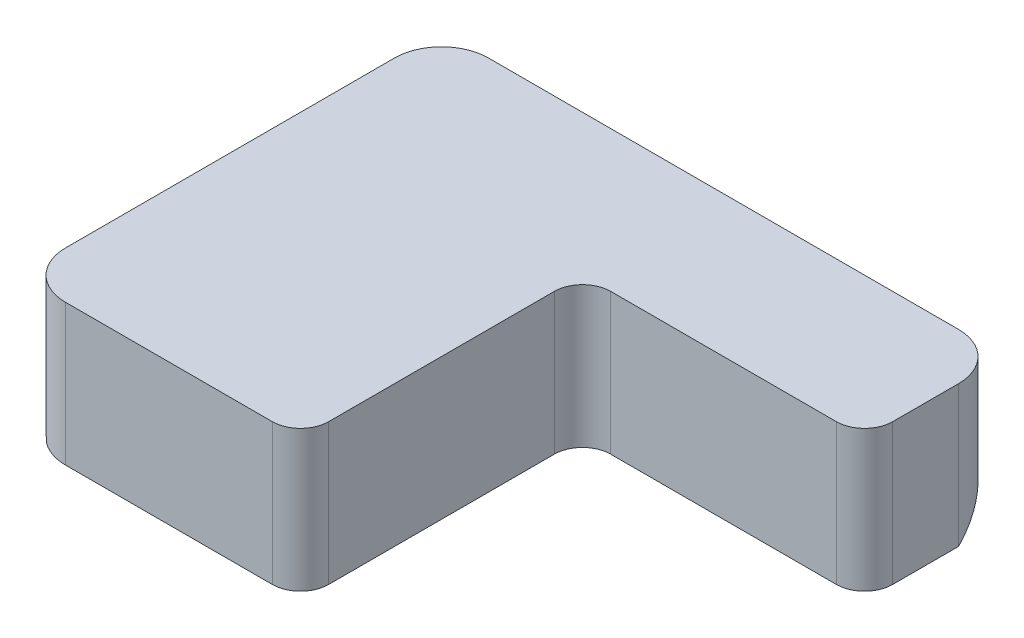
SolidWorks part; units mm, degrees
ref_plane "Front Plane" through (0, 0, 0) normal (0, 0, 1) x (1, 0, 0)
ref_plane "Top Plane" through (0, 0, 0) normal (0, 1, 0) x (1, 0, 0)
ref_plane "Right Plane" through (0, 0, 0) normal (1, 0, 0) x (0, 0, -1)
sketch "Sketch1" plane through (0, 0, 0) normal (0, 1, 0) x (1, 0, 0)
  line L0 (0, 0) -> (30, 0)
  line L1 (30, 0) -> (30, 15)
  line L2 (30, 15) -> (-30, 15)
  line L3 (-30, 15) -> (-30, -30)
  line L4 (-30, -30) -> (0, -30)
  line L5 (0, -30) -> (0, 0)
  dimension "D1" = 15
  dimension "D2" = 30
  dimension "D3" = 30
  dimension "D4" = 30
extrude "Boss-Extrude1" add sketch "Sketch1" along normal blind 15
chamfer "Chamfer1" distance 5 angle 45 2 edges at (0, 0, -15) (-30, 0, 7.5)
chamfer "Chamfer2" distance 2 angle 45 1 edges at (-30, 0, 10)
fillet "Fillet1" radius 3 3 edges at (30, 7.5, 0) (0, 7.5, 30) (0, 7.5, 0)
fillet "Fillet2" radius 5 3 edges at (30, 10, -15) (-30, 8.5, 30) (-30, 10, -15)
